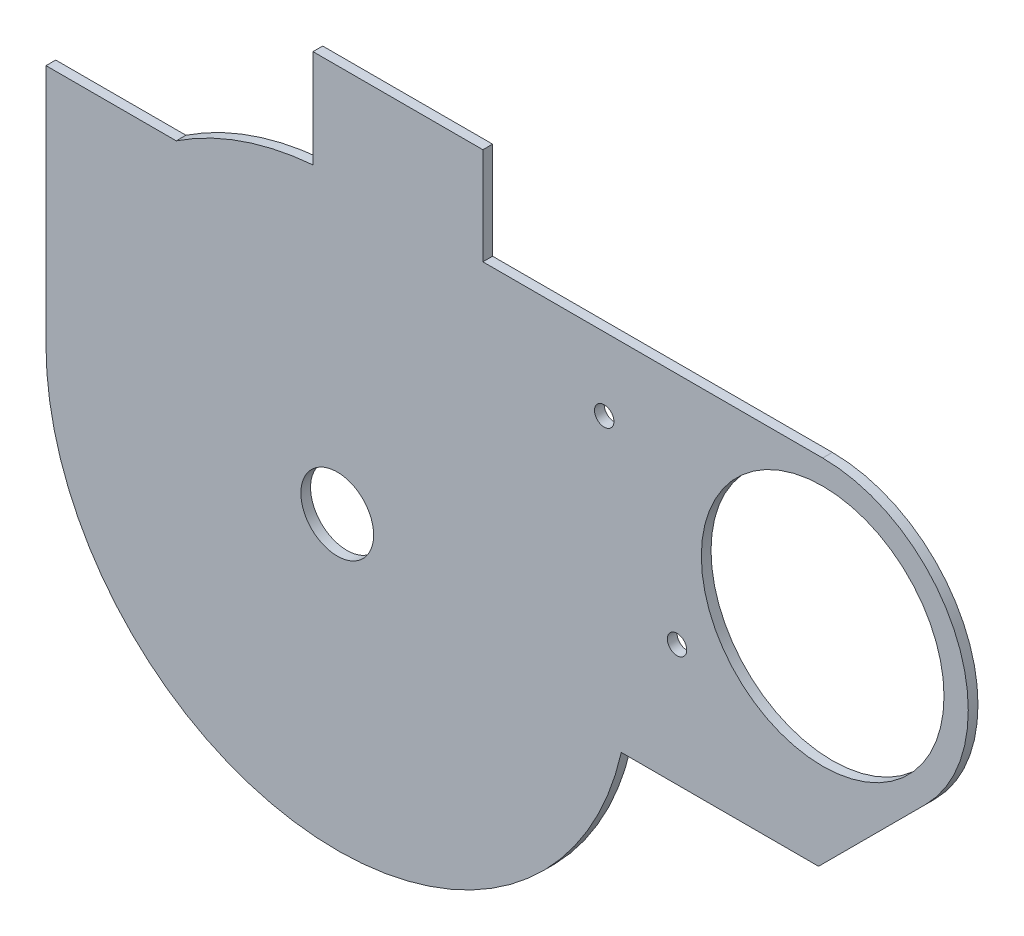
SolidWorks part; units mm, degrees
ref_plane "前视基准面" through (0, 0, 0) normal (0, 0, 1) x (1, 0, 0)
ref_plane "上视基准面" through (0, 0, 0) normal (0, 1, 0) x (1, 0, 0)
ref_plane "右视基准面" through (0, 0, 0) normal (1, 0, 0) x (0, 0, -1)
sketch "Sketch1" plane through (0, 0, 0) normal (0, 0, 1) x (1, 0, 0)
  line L0 (-26.5591, 60) -> (97.717, 60) construction
  line L3 (-33.1662, 50) -> (-60, 50)
  line L4 (-60, 0) -> (-60, 50)
  line L5 (100, 60) -> (0, 60)
  line L6 (73.5456, -38.8808) -> (87.301, -25.1254) construction
  line L7 (106.8791, 60) -> (171.5951, 60) construction
  line L10 (99.1522, -13.2742) -> (121.2132, 8.7868)
  line L11 (58.5132, -13.2742) -> (99.1522, -13.2742)
  arc A0 (0, 60) -> (58.5132, -13.2742) centre (0, 0) ccw
  circle A2 centre (0, 0) radius 7.5
  arc A4 (121.2132, 8.7868) -> (100, 60) centre (100, 30) ccw
  circle A7 centre (100, 30) radius 25
  dimension "D1" = 120
  dimension "D2" = 100
  dimension "D5" = 60
extrude "Boss-Extrude1" add sketch "Sketch1" along normal blind 2
sketch "Sketch2" plane through (0, 0, 2) normal (0, 0, 1) x (1, 0, 0)
  line L0 (100, 60) -> (0, 60) construction
  line L1 (-60, 0) -> (-60, 50) construction
  line L5 (125, 30) -> (100, 5) construction
  line L6 (115.7514, 14.2486) -> (82.3223, 47.6777) construction
  line L7 (58.5132, -13.2742) -> (99.1522, -13.2742) construction
  circle A1 centre (0, 0) radius 57
  circle A2 centre (55, 45) radius 2
  circle A3 centre (70, 11.7258) radius 2
  circle A4 centre (96.4645, 33.5355) radius 15
  circle A5 centre (100, 30) radius 25 construction
  dimension "D1" = 15
  dimension "D4" = 130
  dimension "D5" = 20
  dimension "D2" = 115
  dimension "D3" = 25
extrude "Cut-Extrude1" cut sketch "Sketch2" against normal up to next contours A2 | A3
sketch "Sketch3" plane through (0, 0, 0) normal (0, 0, -1) x (-1, 0, 0)
  line L0 (-30, 18.0278) -> (-30, 80)
  line L1 (-30, 80) -> (5, 80)
  line L2 (5, 80) -> (5, 48)
  line L3 (5, 48) -> (15.6215, 31.3204)
  line L4 (-30, 60) -> (0, 60)
  line L5 (-100, 60) -> (0, 60) construction
  arc A1 (15.6215, 31.3204) -> (-30, 18.0278) centre (0, 0) ccw
  arc A2 (33.1662, 50) -> (0, 60) centre (0, 0) ccw construction
  arc A3 (5, 59.7913) -> (0, 60) centre (0, 0) ccw
  arc M10 (33.1662, 50) -> (0, 60) centre (0, 0) ccw
  line M11 (0, 60) -> (-100, 60)
extrude "Boss-Extrude2" add sketch "Sketch3" against normal blind 2 contours L2 L1 L0 M11 M10
sketch "Sketch4" plane through (0, 0, 0) normal (0, 0, -1) x (-1, 0, 0)
  line L0 (-30, 80) -> (5, 80) construction
  line L1 (5, 80) -> (5, 48) construction
  line L3 (-20, 65.5961) -> (-5, 65.5961)
  line L4 (-20, 65.5961) -> (-20, 63.5961)
  line L5 (-20, 63.5961) -> (-5, 63.5961)
  line L6 (-5, 65.5961) -> (-5, 63.5961)
  line L7 (-20, 65.5961) -> (-5, 63.5961) construction
  line L8 (-20, 63.5961) -> (-5, 65.5961) construction
  line L9 (-13.5, 72.0961) -> (-11.5, 72.0961)
  line L10 (-13.5, 72.0961) -> (-13.5, 57.0961)
  line L11 (-13.5, 57.0961) -> (-11.5, 57.0961)
  line L12 (-11.5, 72.0961) -> (-11.5, 57.0961)
  line L13 (-13.5, 72.0961) -> (-11.5, 57.0961) construction
  line L14 (-13.5, 57.0961) -> (-11.5, 72.0961) construction
  point P5 (-12.5, 64.5961)
  point P10 (-12.5, 80)
  point P11 (-12.5, 64.5961)
  dimension "D1" = 15
  dimension "D2" = 2
  dimension "D3" = 0
  dimension "D4" = 15
  dimension "D5" = 2
extrude "Boss-Extrude3" add sketch "Sketch4" along normal blind 1 contours L12 L9 L10 L3 | L10 L3 L4 L5 | L12 L3 L10 L5 | L3 L12 L5 L6 | L12 L5 L10 L11
